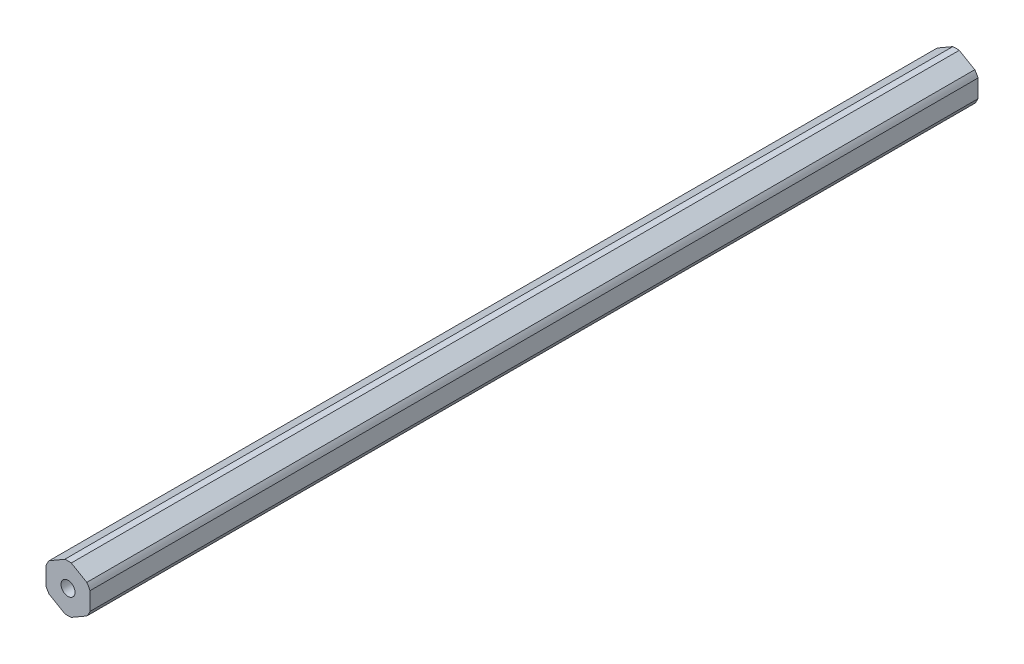
SolidWorks part; units mm, degrees
material "7075-T6 (SN)"
ref_plane "Front Plane" through (0, 0, 0) normal (0, 0, 1) x (1, 0, 0)
ref_plane "Top Plane" through (0, 0, 0) normal (0, 1, 0) x (1, 0, 0)
ref_plane "Right Plane" through (0, 0, 0) normal (1, 0, 0) x (0, 0, -1)
sketch "Sketch1" plane through (0, 0, 0) normal (0, 0, 1) x (1, 0, 0)
  line L1 (0, 7.3323) -> (-6.35, 3.6662)
  line L2 (-6.35, 3.6662) -> (-6.35, -3.6662)
  line L3 (-6.35, -3.6662) -> (0, -7.3323)
  line L4 (0, -7.3323) -> (6.35, -3.6662)
  line L5 (6.35, -3.6662) -> (6.35, 3.6662)
  line L6 (6.35, 3.6662) -> (0, 7.3323)
  circle A0 centre (0, 0) radius 6.35 construction
  circle A1 centre (0, 0) radius 6.858
  dimension "D1" = 12.7
  dimension "D2" = 13.716
extrude "Boss-Extrude1" add sketch "Sketch1" along normal mid plane 256.159 contours L5 A1 L6 L1 L2 L3 L4
sketch "Sketch2" plane through (0, 0, 128.0795) normal (0, 0, 1) x (1, 0, 0)
  circle A0 centre (0, 0) radius 2.0193
  dimension "D1" = 4.0386
extrude "Cut-Extrude1" cut sketch "Sketch2" against normal through all
